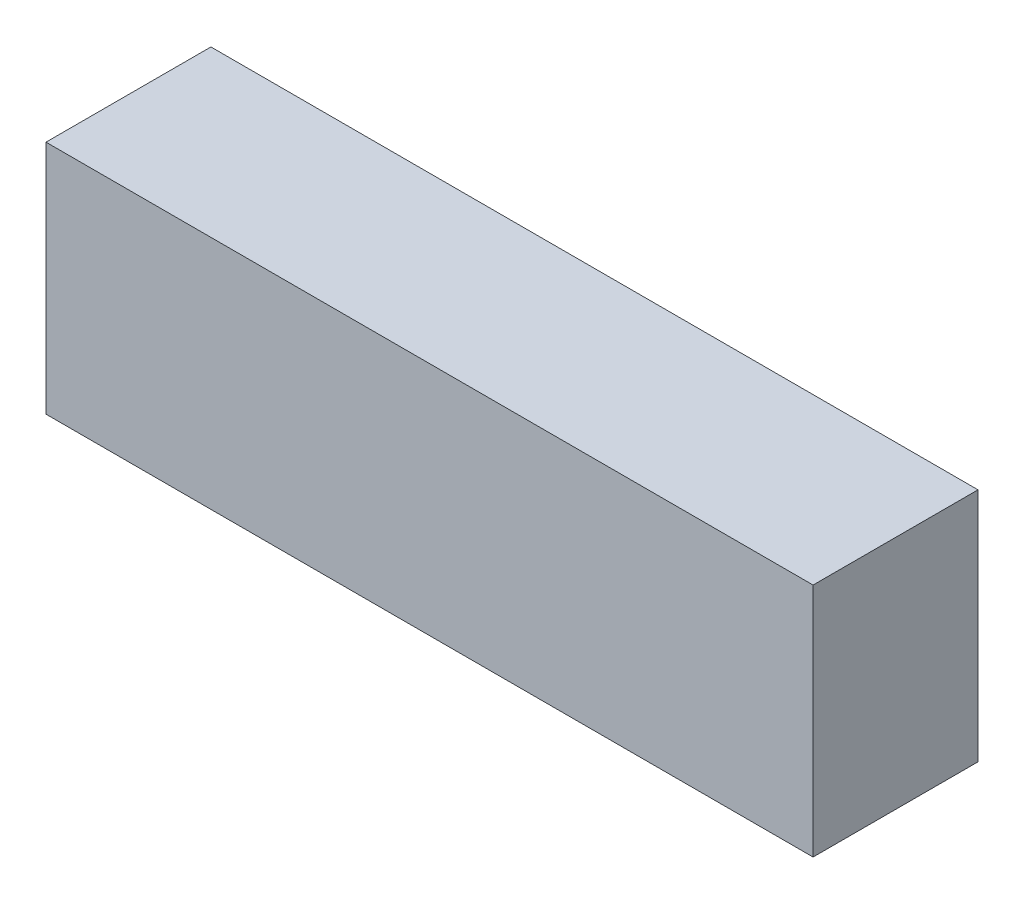
SolidWorks part; units mm, degrees
ref_plane "Спереди" through (0, 0, 0) normal (0, 0, 1) x (1, 0, 0)
ref_plane "Сверху" through (0, 0, 0) normal (0, 1, 0) x (1, 0, 0)
ref_plane "Справа" through (0, 0, 0) normal (1, 0, 0) x (0, 0, -1)
sketch "Эскиз1" plane through (0, 0, 0) normal (0, 0, 1) x (1, 0, 0)
  line L1 (-16.2799, 5) -> (16.2799, 5)
  line L2 (-16.2799, 5) -> (-16.2799, -5)
  line L3 (-16.2799, -5) -> (16.2799, -5)
  line L4 (16.2799, 5) -> (16.2799, -5)
  line L5 (-16.2799, 5) -> (16.2799, -5) construction
  line L6 (-16.2799, -5) -> (16.2799, 5) construction
  point P0 (0, 0)
extrude "Вытянуть1" add sketch "Эскиз1" along normal blind 7
